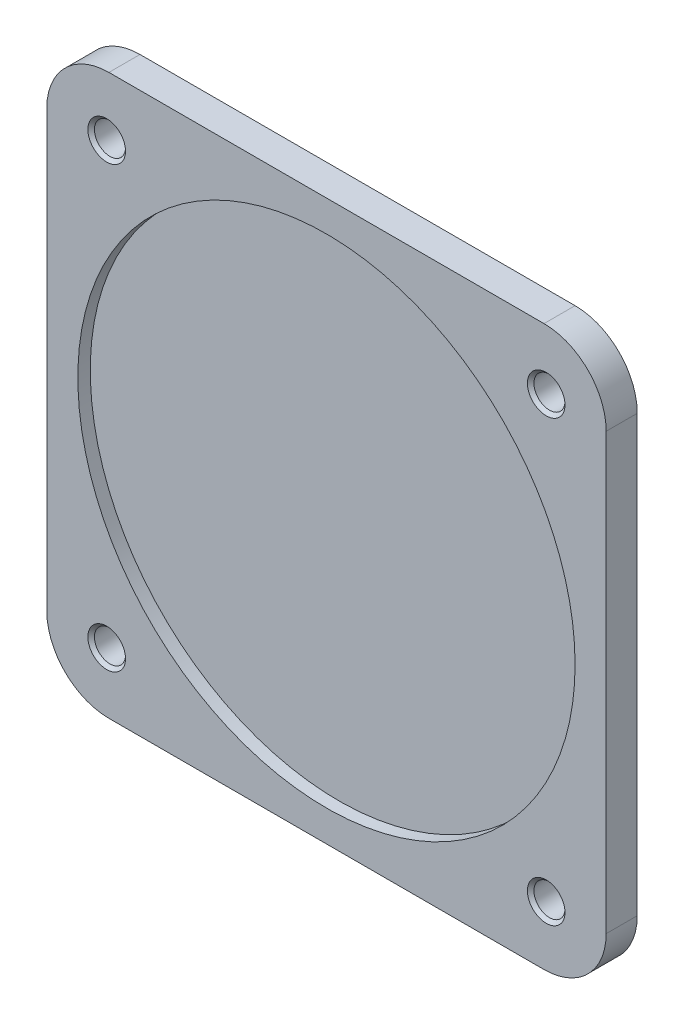
SolidWorks part; units mm, degrees
ref_plane "前视基准面" through (0, 0, 0) normal (0, 0, 1) x (1, 0, 0)
ref_plane "上视基准面" through (0, 0, 0) normal (0, 1, 0) x (1, 0, 0)
ref_plane "右视基准面" through (0, 0, 0) normal (1, 0, 0) x (0, 0, -1)
sketch "草图1" plane through (0, 0, 0) normal (0, 0, 1) x (1, 0, 0)
  line L1 (-45, 45) -> (45, 45)
  line L2 (-45, 45) -> (-45, -45)
  line L3 (-45, -45) -> (45, -45)
  line L4 (45, 45) -> (45, -45)
  line L5 (-45, 45) -> (45, -45) construction
  line L6 (-45, -45) -> (45, 45) construction
  point P0 (0, 0)
  dimension "D1" = 90
  dimension "D2" = 90
extrude "凸台-拉伸1" add sketch "草图1" along normal blind 5
fillet "圆角1" radius 10 4 edges at (45, -45, 2.5) (-45, -45, 2.5) (45, 45, 2.5) (-45, 45, 2.5)
sketch "草图2" plane through (0, 0, 5) normal (0, 0, 1) x (1, 0, 0)
  line L0 (0, 0) -> (-42.0711, 42.0711) construction
  line L1 (-42.0711, -42.0711) -> (42.0711, 42.0711) construction
  line L2 (0, 0) -> (42.0711, -42.0711) construction
  circle A0 centre (0, 0) radius 50 construction
  arc A1 (-35, 45) -> (-45, 35) centre (-35, 35) ccw construction
  arc A2 (-45, -35) -> (-35, -45) centre (-35, -35) ccw construction
  arc A3 (45, 35) -> (35, 45) centre (35, 35) ccw construction
  arc A4 (35, -45) -> (45, -35) centre (35, -35) ccw construction
  point P21 (-35.3553, 35.3553)
  point P23 (35.3553, 35.3553)
  point P25 (-35.3553, -35.3553)
  point P27 (35.3553, -35.3553)
  dimension "D1" = 100
hole_wizard "M6 螺纹孔1" positions "草图2" profile "草图3" tap size "M6" standard "GB"
sketch "草图3" plane through (35.3553, -35.3553, 5) normal (1, 0, 0) x (0, -1, 0)
  line L0 (0, 0) -> (0, 18.5022)
  line L1 (0, 18.5022) -> (2.5, 17)
  line L2 (2.5, 17) -> (2.5, 0.525)
  line L3 (2.5, 0.525) -> (3.025, 0)
  line L5 (3.025, 0) -> (0, 0)
  line L6 (-2.5, 0.525) -> (-3.025, 0) construction
  line L10 (0, 18.5022) -> (-2.5, 17) construction
  line L11 (0, -6.35) -> (0, 107.95) construction
  dimension "螺纹孔钻头直径" = 5
  dimension "螺纹孔钻头深度" = 17
  dimension "近端锥形沉头孔直径" = 6.05
  dimension "近端锥形沉头孔角度" = 90
  dimension "导头角度" = 118
cosmetic thread "孔螺纹线1" parameters "D1"=12, "D2"=6
cosmetic thread "孔螺纹线2" parameters "D1"=12, "D2"=6
cosmetic thread "孔螺纹线3" parameters "D1"=12, "D2"=6
cosmetic thread "孔螺纹线4" parameters "D1"=12, "D2"=6
sketch "草图4" plane through (0, 0, 5) normal (0, 0, 1) x (1, 0, 0)
  circle A0 centre (0, 0) radius 40
  dimension "D1" = 80
extrude "切除-拉伸1" cut sketch "草图4" against normal blind 2
